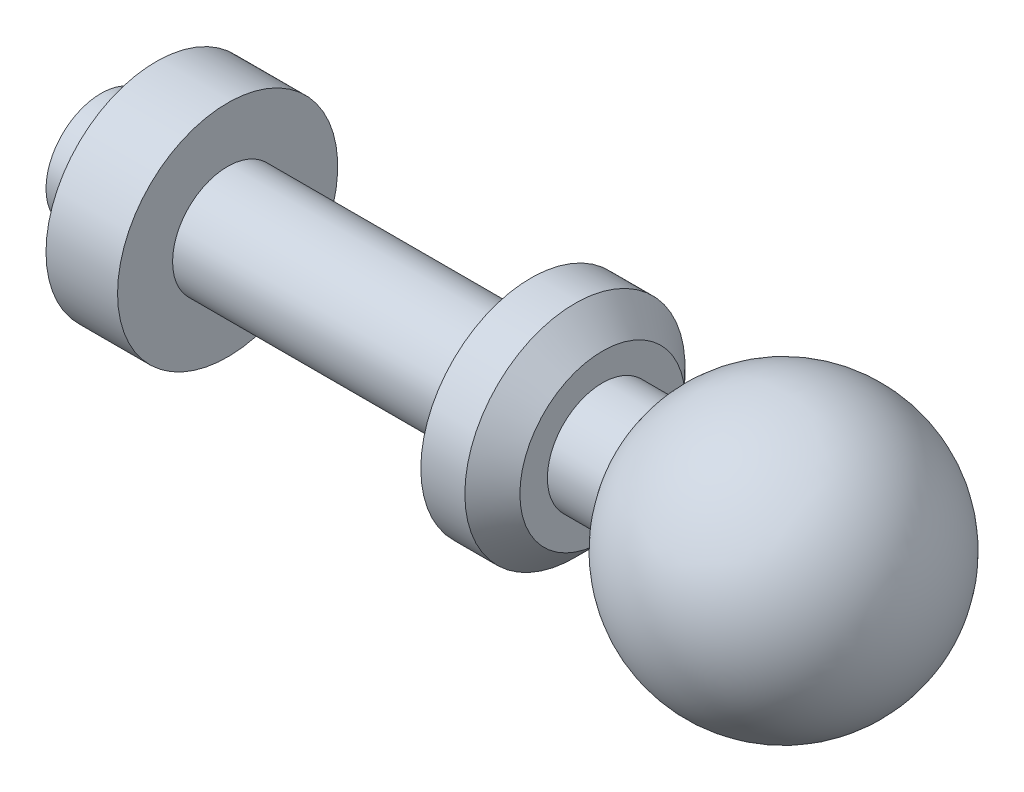
SolidWorks part; units mm, degrees
ref_plane "Front Plane" through (0, 0, 0) normal (0, 0, 1) x (1, 0, 0)
ref_plane "Top Plane" through (0, 0, 0) normal (0, 1, 0) x (1, 0, 0)
ref_plane "Right Plane" through (0, 0, 0) normal (1, 0, 0) x (0, 0, -1)
sketch "Sketch1" plane through (0, 0, 0) normal (0, 0, 1) x (1, 0, 0)
  line L0 (0, 0) -> (0, 10)
  line L1 (0, 10) -> (10, 10)
  line L2 (10, 10) -> (10, 20)
  line L3 (10, 20) -> (23, 20)
  line L4 (23, 20) -> (23, 10)
  line L5 (23, 10) -> (78.1, 10)
  line L6 (78.1, 10) -> (78.1, 20)
  line L7 (78.1, 20) -> (86.1, 20)
  line L8 (91.1, 15) -> (91.1, 10)
  line L9 (91.1, 10) -> (101.1, 10)
  line L10 (0, 0) -> (149.0129, 0)
  line L11 (0, 0) -> (215.2528, 0) construction
  line L12 (86.1, 20) -> (91.1, 15)
  arc A0 (149.0129, 0) -> (101.1, 10) centre (124.0129, 0) ccw
  point P9 (91.1, 20)
  dimension "D7" = 25
  dimension "D1" = 10
  dimension "D2" = 13
  dimension "D3" = 20
  dimension "D4" = 10
  dimension "D5" = 55.1
  dimension "D6" = 10
revolve "Revolve1" add sketch "Sketch1" angle 360 about L11
